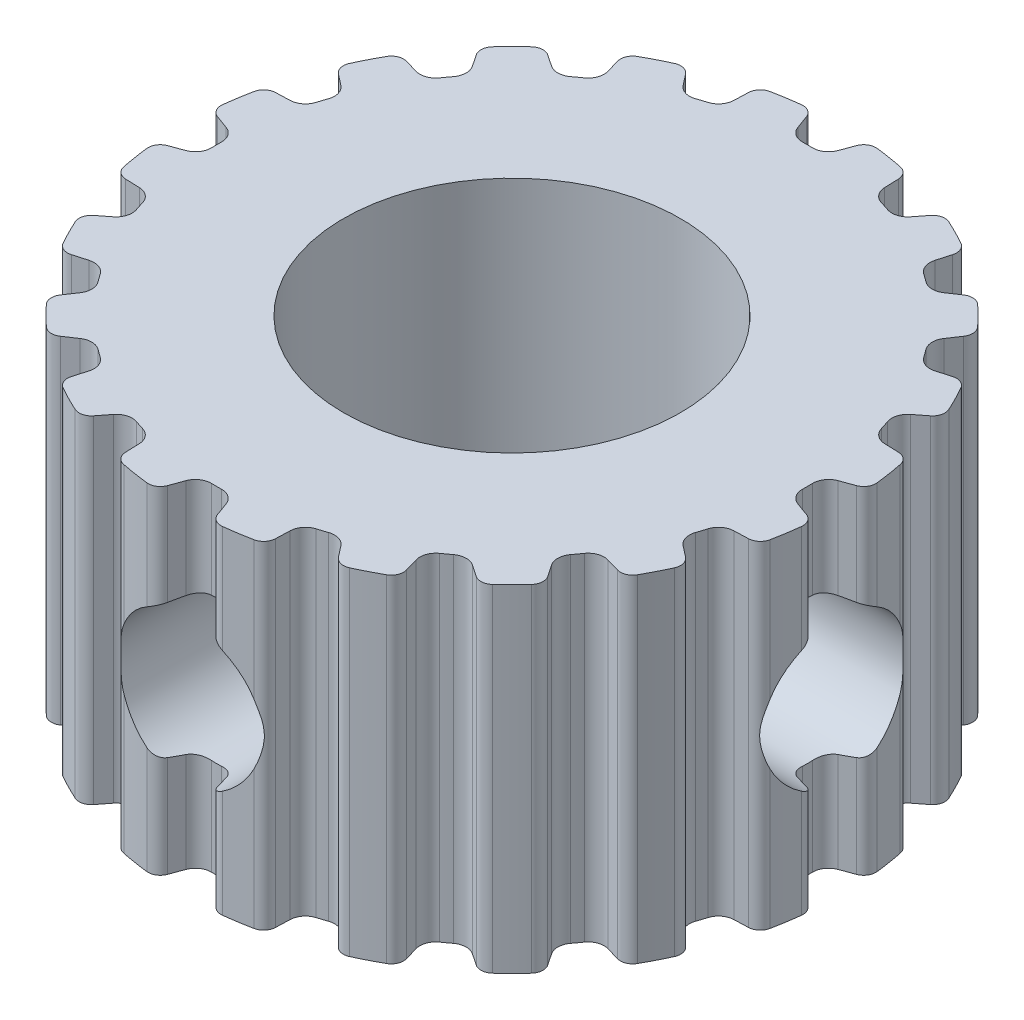
SolidWorks part; units mm, degrees
ref_plane "Front Plane" through (0, 0, 0) normal (0, 0, 1) x (1, 0, 0)
ref_plane "Top Plane" through (0, 0, 0) normal (0, 1, 0) x (1, 0, 0)
ref_plane "Right Plane" through (0, 0, 0) normal (1, 0, 0) x (0, 0, -1)
sketch "Sketch1" plane through (0, 0, 0) normal (0, 1, 0) x (1, 0, 0)
  circle A0 centre (0, 0) radius 6.215
  dimension "D1" = 12.43
extrude "Boss-Extrude1" add sketch "Sketch1" along normal blind 6.35
sketch "Sketch2" plane through (0, 0, 0) normal (0, 1, 0) x (1, 0, 0)
  line L0 (0.305, 5.5667) -> (0.5327, 6.1921)
  line L1 (-0.305, 5.5667) -> (-0.5327, 6.1921)
  line L2 (0, 0) -> (0, 6.215) construction
  circle A2 centre (0, 0) radius 6.215 construction
  circle A3 centre (0, 0) radius 5.575
  arc A4 (0.305, 5.5667) -> (-0.305, 5.5667) centre (0, 0) ccw
  arc A5 (0.5327, 6.1921) -> (-0.5327, 6.1921) centre (0, 0) ccw
  dimension "D2" = 20
  dimension "D3" = 0.61
  dimension "D1" = 0.64
extrude "Cut-Extrude1" cut sketch "Sketch2" along normal through all
fillet "Fillet1" radius 0.3 2 edges at (0.305, 3.175, -5.5667) (-0.305, 3.175, -5.5667)
fillet "Fillet2" radius 0.23 2 edges at (0.5327, 3.175, -6.1921) (-0.5327, 3.175, -6.1921)
pattern_circular "CirPattern1" count 20 over 360 about axis through (0, 0, 0) along (0, 1, 0) of "Fillet2", "Fillet1", "Cut-Extrude1"
sketch "Sketch4" plane through (0, 0, 0) normal (0, 1, 0) x (1, 0, 0)
  circle A0 centre (0, 0) radius 3.175
  dimension "D1" = 6.35
extrude "Cut-Extrude2" cut sketch "Sketch4" along normal through all
hole_wizard "#6-32 Tapped Hole1" positions "Sketch6" profile "Sketch8" tap size "#6-32" standard "ANSI Inch"
sketch "Sketch6" plane through (0, 0, 0) normal (0, 0, 1) x (1, 0, 0)
  line L0 (0, 6.35) -> (0, 0) construction
  line L1 (0, 0) -> (0, 6.35) construction
  line L2 (3.175, 6.35) -> (-3.175, 6.35) construction
  point P0 (0, 3.175)
  point P13 (0, 2.693)
  point P14 (0, 3.175)
sketch "Sketch8" plane through (0, 3.175, 0) normal (1, 0, 0) x (0, 1, 0)
  line L0 (0, 0) -> (0, 6.1754)
  line L1 (0, 6.1754) -> (1.3525, 6.1754)
  line L2 (1.3525, 6.1754) -> (1.3525, 0)
  line L5 (1.3525, 0) -> (0, 0)
  line L11 (0, -6.35) -> (0, 107.95) construction
  dimension "Thru Tap Drill Dia." = 2.7051
  dimension "Thru Tap Drill Depth" = 6.1754
cosmetic thread "Hole Thread1" parameters "D2"=3.5052
pattern_circular "CirPattern2" count 2 every 90 about axis through (0, 6.35, 0) along (0, -1, 0) of "#6-32 Tapped Hole1"
cosmetic thread "Hole Thread2" parameters "D2"=3.5052
sketch "Sketch9" plane through (0, 0, 0) normal (0, 1, 0) x (1, 0, 0)
  circle A0 centre (0, 0) radius 6.47 construction
  dimension "D1" = 12.94
equation "\"OD\"=12.43"
equation "\"D1@Sketch1\"=\"OD\""
